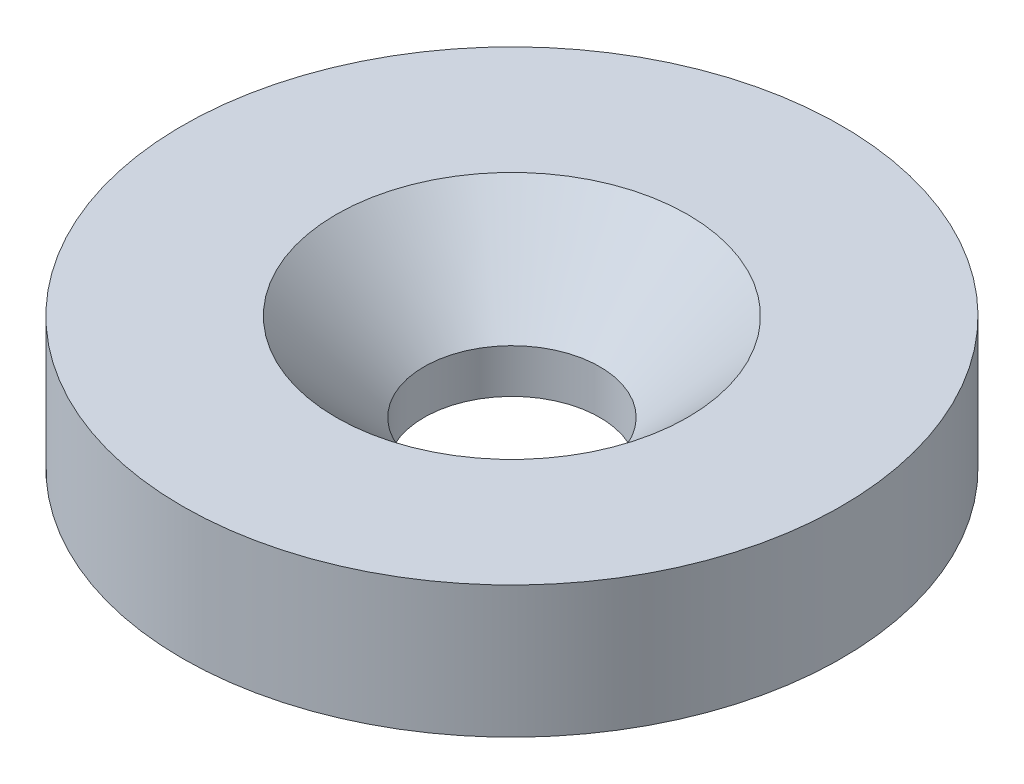
SolidWorks part; units mm, degrees
ref_plane "Piano frontale" through (0, 0, 0) normal (0, 0, 1) x (1, 0, 0)
ref_plane "Piano superiore" through (0, 0, 0) normal (0, 1, 0) x (1, 0, 0)
ref_plane "Piano destro" through (0, 0, 0) normal (1, 0, 0) x (0, 0, -1)
sketch "Schizzo1" plane through (0, 0, 0) normal (0, 1, 0) x (1, 0, 0)
  circle A0 centre (0, 0) radius 7.5
  dimension "D1" = 15
extrude "Estrusione-Estrusione1" add sketch "Schizzo1" along normal blind 3
hole_wizard "Foro svasato per Vite M4 a testa svasata cilindrica1" positions "Schizzo3D1" profile "Schizzo3" countersink size "M4" standard "DIN"
sketch3d "Schizzo3D1"
  point P4 (0, 3, 0)
  point P7 (0.0562, 3, 0.0261)
  point P8 (0, 0, 0)
  point P9 (0.1148, 3, -0.0583)
  point P10 (-0.178, 3, 0.4566)
sketch "Schizzo3" plane through (0, 3, 0) normal (1, 0, 0) x (0, 0, 1)
  line L0 (0, 0) -> (0, 10.2017)
  line L1 (0, 10.2017) -> (2, 9)
  line L2 (2, 9) -> (2, 2)
  line L3 (2, 2) -> (4, 0)
  line L5 (4, 0) -> (0, 0)
  line L6 (-2, 2) -> (-4, 0) construction
  line L10 (0, 10.2017) -> (-2, 9) construction
  line L11 (0, -6.35) -> (0, 107.95) construction
  dimension "Hole Dia." = 4
  dimension "Hole Depth" = 9
  dimension "Near C'Sink Dia." = 8
  dimension "Near C'Sink Angle" = 90
  dimension "Drill Angle" = 118
